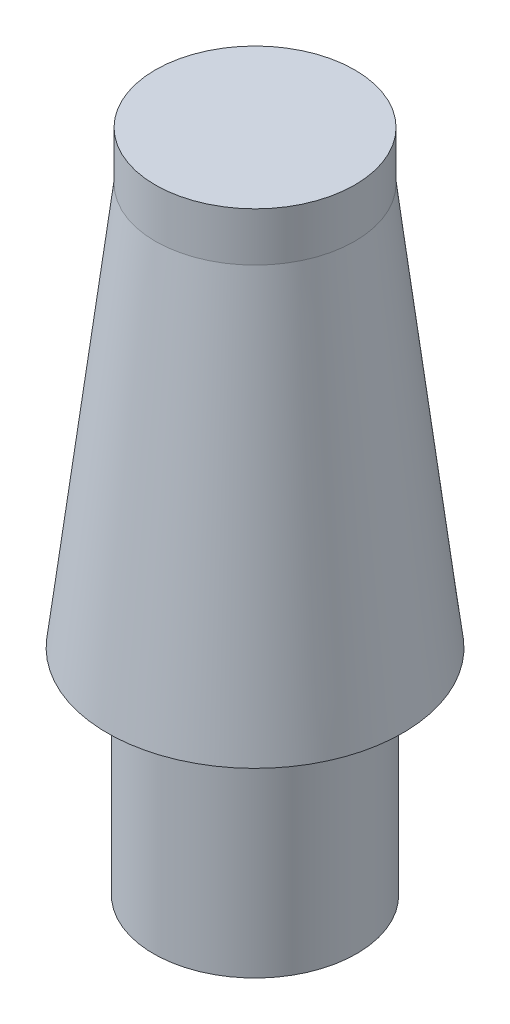
SolidWorks part; units mm, degrees
ref_plane "Front Plane" through (0, 0, 0) normal (0, 0, 1) x (1, 0, 0)
ref_plane "Top Plane" through (0, 0, 0) normal (0, 1, 0) x (1, 0, 0)
ref_plane "Right Plane" through (0, 0, 0) normal (1, 0, 0) x (0, 0, -1)
sketch "Sketch1" plane through (0, 0, 0) normal (0, 0, 1) x (1, 0, 0)
  line L0 (0, 0) -> (0, 228.6) construction
  line L1 (34.925, 0) -> (34.925, 73.66)
  line L2 (34.925, 73.66) -> (50.8, 73.66)
  line L3 (50.8, 73.66) -> (34.29, 211.836)
  line L4 (34.29, 211.836) -> (34.29, 228.6)
  line L5 (34.29, 228.6) -> (0, 228.6)
  line L6 (34.925, 0) -> (0, 0)
  line L7 (0, 0) -> (0, 228.6)
  dimension "D1" = 228.6
  dimension "D2" = 69.85
  dimension "D3" = 73.66
  dimension "D4" = 101.6
  dimension "D5" = 68.58
  dimension "D6" = 16.764
revolve "Revolve1" add sketch "Sketch1" angle 360 about L0
sketch "Sketch3" plane through (0, 0, 0) normal (0, -1, 0) x (1, 0, 0)
  circle A2 centre (0, 0) radius 30.48
  circle A3 centre (0, 0) radius 30.48
  dimension "D1" = 4.445
extrude "Cut-Extrude1" cut sketch "Sketch3" against normal up to surface (73.66 mm away) up to face at (0, 73.66, -50.8)
